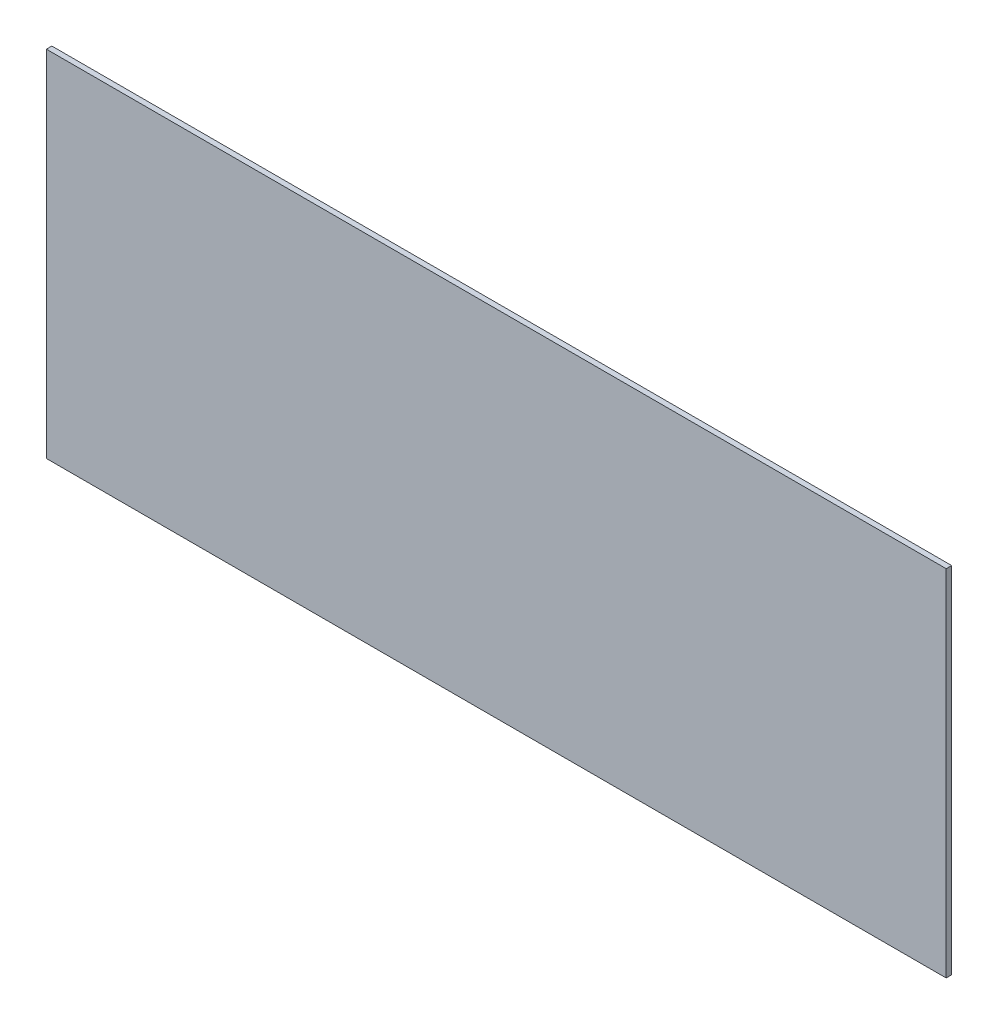
SolidWorks part; units mm, degrees
ref_plane "Front Plane" through (0, 0, 0) normal (0, 0, 1) x (1, 0, 0)
ref_plane "Top Plane" through (0, 0, 0) normal (0, 1, 0) x (1, 0, 0)
ref_plane "Right Plane" through (0, 0, 0) normal (1, 0, 0) x (0, 0, -1)
sketch "Sketch2" plane through (0, 0, 0) normal (0, 0, 1) x (1, 0, 0)
  line L1 (-82.5, -32.5) -> (82.5, -32.5)
  line L2 (-82.5, -32.5) -> (-82.5, 32.5)
  line L3 (-82.5, 32.5) -> (82.5, 32.5)
  line L4 (82.5, -32.5) -> (82.5, 32.5)
  line L5 (-82.5, -32.5) -> (82.5, 32.5) construction
  line L6 (-82.5, 32.5) -> (82.5, -32.5) construction
  point P0 (0, 0)
  dimension "D1" = 165
  dimension "D2" = 65
extrude "Boss-Extrude1" add sketch "Sketch2" along normal blind 1
